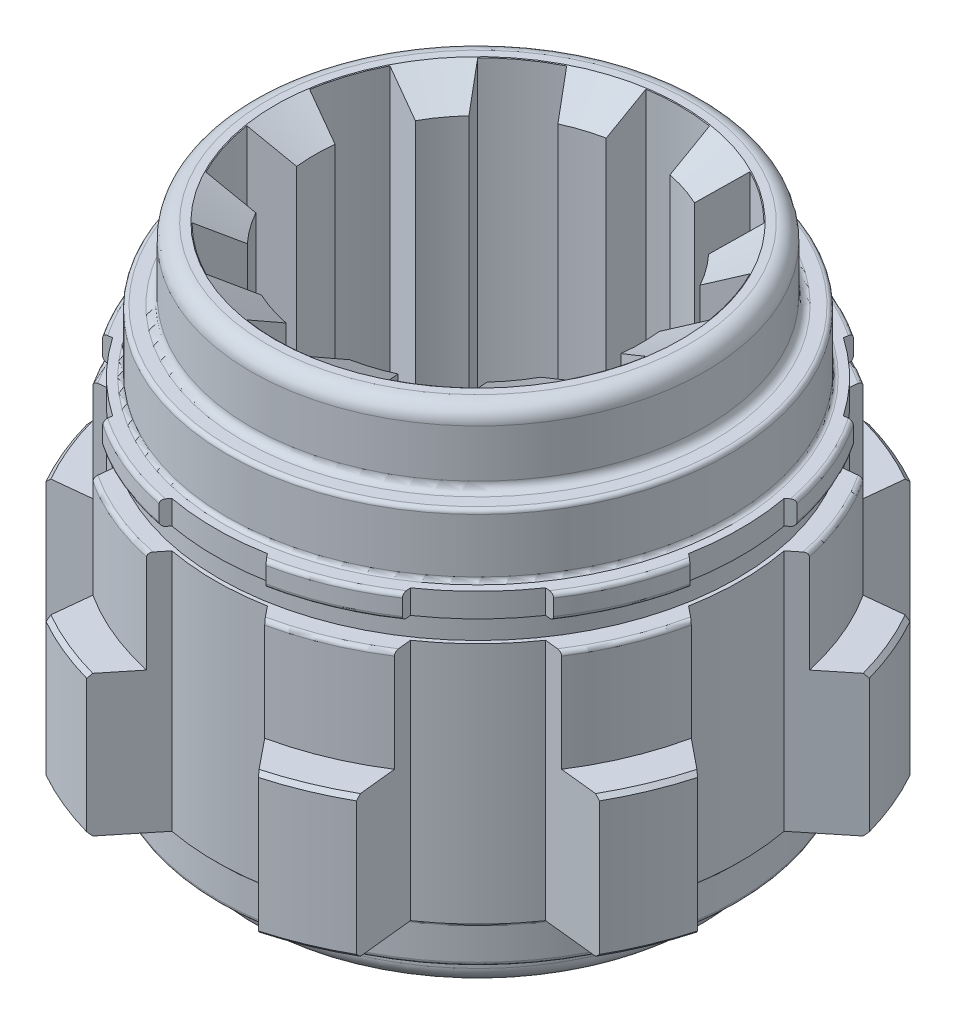
SolidWorks part; units mm, degrees
ref_plane "Plano frontal" through (0, 0, 0) normal (0, 0, 1) x (1, 0, 0)
ref_plane "Plano superior" through (0, 0, 0) normal (0, 1, 0) x (1, 0, 0)
ref_plane "Plano direito" through (0, 0, 0) normal (1, 0, 0) x (0, 0, -1)
sketch "Esboço1" plane through (0, 0, 0) normal (0, 0, 1) x (1, 0, 0)
  line L0 (0, -54.4613) -> (0, 50.8185) construction
  line L1 (20.5, 50.8185) -> (28.5, 50.8185)
  line L2 (28.5, 50.8185) -> (28.5, 41.8185)
  line L3 (28.5, 41.8185) -> (31.5, 41.8185)
  line L4 (31.5, 41.8185) -> (31.5, 34.0185)
  line L5 (31.5, 34.0185) -> (34, 34.0185)
  line L6 (34, 34.0185) -> (34, 31.0185)
  line L7 (34, 31.0185) -> (32.5, 31.0185)
  line L8 (32.5, 31.0185) -> (32.5, 28.3185)
  line L9 (32.5, 28.3185) -> (35, 28.3185)
  line L10 (35, 28.3185) -> (35, 15.5185)
  line L11 (35, 15.5185) -> (39.85, 15.5185)
  line L12 (39.85, 15.5185) -> (39.85, -2.1815)
  line L13 (39.85, -2.1815) -> (32.5, -2.1815)
  line L14 (32.5, -2.1815) -> (32.5, -7.1815)
  line L15 (32.5, -7.1815) -> (28.5, -7.1815)
  line L16 (28.5, -7.1815) -> (28.5, -12.1815)
  line L17 (28.5, -12.1815) -> (20.5, -12.1815)
  line L18 (20.5, -12.1815) -> (20.5, 50.8185)
  dimension "D1" = 20.5
  dimension "D2" = 28.5
  dimension "D3" = 31.5
  dimension "D4" = 34
  dimension "D5" = 32.5
  dimension "D6" = 35
  dimension "D7" = 39.85
  dimension "D8" = 32.5
  dimension "D9" = 28.5
  dimension "D10" = 5
  dimension "D11" = 5
  dimension "D12" = 17.7
  dimension "D13" = 3
  dimension "D14" = 2.7
  dimension "D15" = 18.5
  dimension "D16" = 7.8
  dimension "D17" = 63
revolve "Revolução1" add sketch "Esboço1" angle 360 about L0
fillet "Filete1" radius 2 1 edges at (0, 50.8185, -28.5)
fillet "Filete2" radius 1 1 edges at (0, 41.8185, -28.5)
fillet "Filete3" radius 0.5 5 edges at (0, 28.3185, -35) (0, 31.0185, -34) (0, 34.0185, -34) (0, 34.0185, -31.5) (0, 41.8185, -31.5)
chamfer "Chanfro1" distance 0.5 angle 45 2 edges at (0, -2.1815, -39.85) (0, 15.5185, -39.85)
chamfer "Chanfro2" distance 5 angle 30 1 edges at (0, 50.8185, -20.5)
chamfer "Chanfro3" distance 5 angle 30 1 edges at (0, -12.1815, -20.5)
fillet "Filete4" radius 2 1 edges at (0, -12.1815, -28.5)
fillet "Filete5" radius 0.5 3 edges at (0, -2.1815, -32.5) (0, -7.1815, -32.5) (0, -7.1815, -28.5)
sketch "Esboço2" plane through (0, -12.1815, 0) normal (0, -1, 0) x (1, 0, 0)
  line L0 (-6, -32.45) -> (-13.6971, -41.9551)
  line L1 (6, -32.45) -> (13.6971, -41.9551)
  line L2 (0, 0) -> (0, -41.6775) construction
  line L3 (-13.6971, -41.9551) -> (13.6971, -41.9551)
  line L4 (13.6971, -41.9551) -> (14.0281, -41.8701)
  line L5 (-27.1882, -18.7029) -> (-39.3521, -19.9814)
  line L6 (-18.7029, -27.1882) -> (-19.9814, -39.3521)
  line L7 (-39.3521, -19.9814) -> (-19.9814, -39.3521)
  line L8 (-19.9814, -39.3521) -> (-19.6873, -39.526)
  line L9 (-32.45, 6) -> (-41.9551, 13.6971)
  line L10 (-32.45, -6) -> (-41.9551, -13.6971)
  line L11 (-41.9551, 13.6971) -> (-41.9551, -13.6971)
  line L12 (-41.9551, -13.6971) -> (-41.8701, -14.0281)
  line L13 (-18.7029, 27.1882) -> (-19.9814, 39.3521)
  line L14 (-27.1882, 18.7029) -> (-39.3521, 19.9814)
  line L15 (-19.9814, 39.3521) -> (-39.3521, 19.9814)
  line L16 (-39.3521, 19.9814) -> (-39.526, 19.6873)
  line L17 (6, 32.45) -> (13.6971, 41.9551)
  line L18 (-6, 32.45) -> (-13.6971, 41.9551)
  line L19 (13.6971, 41.9551) -> (-13.6971, 41.9551)
  line L20 (-13.6971, 41.9551) -> (-14.0281, 41.8701)
  line L21 (27.1882, 18.7029) -> (39.3521, 19.9814)
  line L22 (18.7029, 27.1882) -> (19.9814, 39.3521)
  line L23 (39.3521, 19.9814) -> (19.9814, 39.3521)
  line L24 (19.9814, 39.3521) -> (19.6873, 39.526)
  line L25 (32.45, -6) -> (41.9551, -13.6971)
  line L26 (32.45, 6) -> (41.9551, 13.6971)
  line L27 (41.9551, -13.6971) -> (41.9551, 13.6971)
  line L28 (41.9551, 13.6971) -> (41.8701, 14.0281)
  line L29 (18.7029, -27.1882) -> (19.9814, -39.3521)
  line L30 (27.1882, -18.7029) -> (39.3521, -19.9814)
  line L31 (19.9814, -39.3521) -> (39.3521, -19.9814)
  line L32 (39.3521, -19.9814) -> (39.526, -19.6873)
  arc A0 (-27.1882, -18.7029) -> (-18.7029, -27.1882) centre (0, 0) ccw
  arc A1 (-6, -32.45) -> (6, -32.45) centre (0, 0) ccw
  arc A2 (-32.45, 6) -> (-32.45, -6) centre (0, 0) ccw
  arc A3 (-18.7029, 27.1882) -> (-27.1882, 18.7029) centre (0, 0) ccw
  arc A4 (6, 32.45) -> (-6, 32.45) centre (0, 0) ccw
  arc A5 (27.1882, 18.7029) -> (18.7029, 27.1882) centre (0, 0) ccw
  arc A6 (32.45, -6) -> (32.45, 6) centre (0, 0) ccw
  arc A7 (18.7029, -27.1882) -> (27.1882, -18.7029) centre (0, 0) ccw
  dimension "D1" = 78
  dimension "D2" = 8
extrude "Corte-extrusão1" cut sketch "Esboço2" against normal through all
sketch "Esboço3" plane through (0, 50.8185, 0) normal (0, 1, 0) x (1, 0, 0)
  line L0 (-4, 25.0831) -> (-4, 18.4053)
  line L1 (0, 0) -> (0, 25.4) construction
  line L2 (-4, 18.4053) -> (4, 18.4053)
  line L3 (4, 18.4053) -> (4, 25.0831)
  line L4 (11.5074, 22.6438) -> (7.5823, 17.2413)
  line L5 (7.5823, 17.2413) -> (14.0544, 12.5391)
  line L6 (14.0544, 12.5391) -> (17.9795, 17.9415)
  line L7 (22.6193, 11.5553) -> (16.2684, 9.4918)
  line L8 (16.2684, 9.4918) -> (18.7406, 1.8833)
  line L9 (18.7406, 1.8833) -> (25.0915, 3.9469)
  line L10 (25.0915, -3.9469) -> (18.7406, -1.8833)
  line L11 (18.7406, -1.8833) -> (16.2684, -9.4918)
  line L12 (16.2684, -9.4918) -> (22.6193, -11.5553)
  line L13 (17.9795, -17.9415) -> (14.0544, -12.5391)
  line L14 (14.0544, -12.5391) -> (7.5823, -17.2413)
  line L15 (7.5823, -17.2413) -> (11.5074, -22.6438)
  line L16 (4, -25.0831) -> (4, -18.4053)
  line L17 (4, -18.4053) -> (-4, -18.4053)
  line L18 (-4, -18.4053) -> (-4, -25.0831)
  line L19 (-11.5074, -22.6438) -> (-7.5823, -17.2413)
  line L20 (-7.5823, -17.2413) -> (-14.0544, -12.5391)
  line L21 (-14.0544, -12.5391) -> (-17.9795, -17.9415)
  line L22 (-22.6193, -11.5553) -> (-16.2684, -9.4918)
  line L23 (-16.2684, -9.4918) -> (-18.7406, -1.8833)
  line L24 (-18.7406, -1.8833) -> (-25.0915, -3.9469)
  line L25 (-25.0915, 3.9469) -> (-18.7406, 1.8833)
  line L26 (-18.7406, 1.8833) -> (-16.2684, 9.4918)
  line L27 (-16.2684, 9.4918) -> (-22.6193, 11.5553)
  line L28 (-17.9795, 17.9415) -> (-14.0544, 12.5391)
  line L29 (-14.0544, 12.5391) -> (-7.5823, 17.2413)
  line L30 (-7.5823, 17.2413) -> (-11.5074, 22.6438)
  arc A0 (11.5074, 22.6438) -> (17.9795, 17.9415) centre (0, 0) cw
  arc A1 (-4, 25.0831) -> (4, 25.0831) centre (0, 0) cw
  arc A2 (22.6193, 11.5553) -> (25.0915, 3.9469) centre (0, 0) cw
  arc A3 (25.0915, -3.9469) -> (22.6193, -11.5553) centre (0, 0) cw
  arc A4 (17.9795, -17.9415) -> (11.5074, -22.6438) centre (0, 0) cw
  arc A5 (4, -25.0831) -> (-4, -25.0831) centre (0, 0) cw
  arc A6 (-11.5074, -22.6438) -> (-17.9795, -17.9415) centre (0, 0) cw
  arc A7 (-22.6193, -11.5553) -> (-25.0915, -3.9469) centre (0, 0) cw
  arc A8 (-25.0915, 3.9469) -> (-22.6193, 11.5553) centre (0, 0) cw
  arc A9 (-17.9795, 17.9415) -> (-11.5074, 22.6438) centre (0, 0) cw
  dimension "D1" = 10
extrude "Corte-extrusão2" cut sketch "Esboço3" against normal through all
